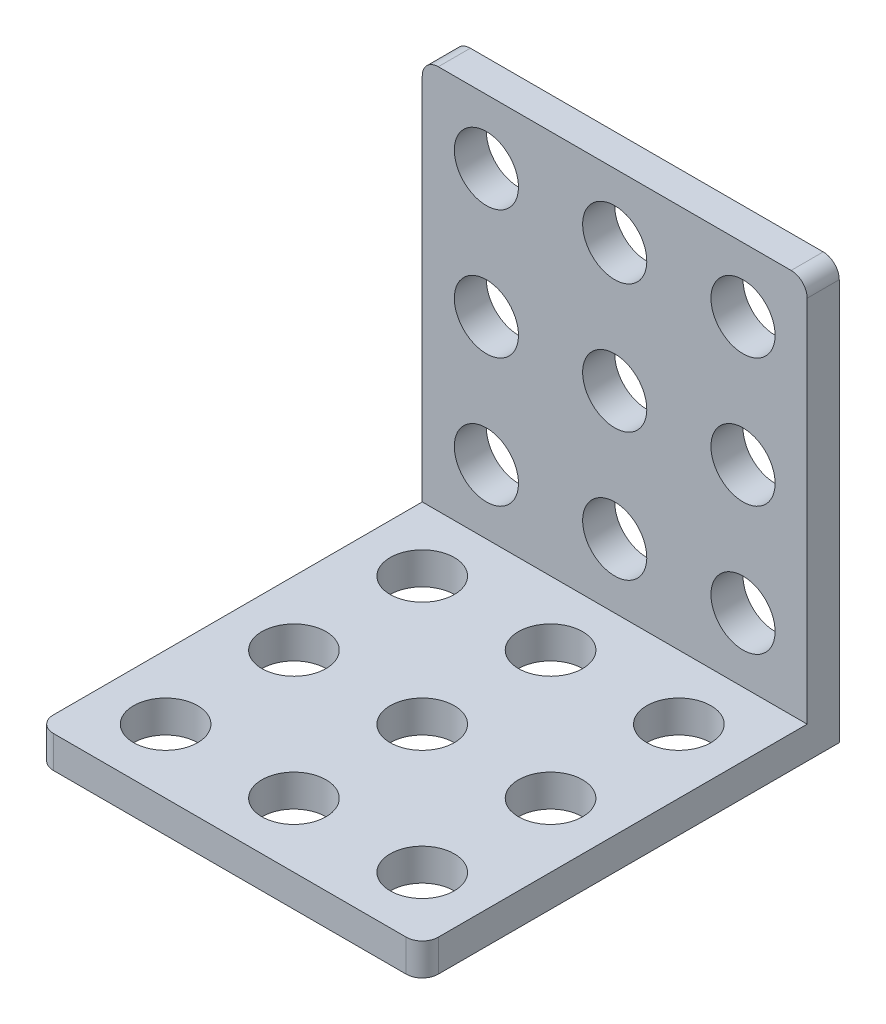
SolidWorks part; units mm, degrees
ref_plane "Спереди" through (0, 0, 0) normal (0, 0, 1) x (1, 0, 0)
ref_plane "Сверху" through (0, 0, 0) normal (0, 1, 0) x (1, 0, 0)
ref_plane "Справа" through (0, 0, 0) normal (1, 0, 0) x (0, 0, -1)
sketch "Эскиз1" plane through (0, 0, 0) normal (1, 0, 0) x (0, 0, -1)
  line L0 (0, 0) -> (-26, 0)
  line L1 (-26, 0) -> (-26, 2)
  line L2 (-26, 2) -> (-2, 2)
  line L3 (-2, 2) -> (-2, 26)
  line L4 (-2, 26) -> (0, 26)
  line L5 (0, 26) -> (0, 0)
  dimension "D1" = 26
  dimension "D2" = 26
  dimension "D3" = 2
extrude "Бобышка-Вытянуть1" add sketch "Эскиз1" along normal blind 24
sketch "Эскиз2" plane through (0, 0, 0) normal (0, 0, 1) x (1, 0, 0)
  line L0 (12, 2) -> (12, 26) construction
  line L1 (0, 26) -> (24, 26) construction
  line L2 (0, 26) -> (0, 2) construction
  line L3 (0, 2) -> (24, 2) construction
  line L4 (24, 26) -> (24, 2) construction
  line L5 (0, 14) -> (24, 14) construction
  line L6 (0, 26) -> (0, 25)
  line L7 (0, 26) -> (1, 26)
  line L8 (24, 26) -> (23, 26)
  line L9 (24, 26) -> (24, 25)
  circle A0 centre (12, 14) radius 2
  circle A1 centre (4, 14) radius 2
  circle A2 centre (20, 14) radius 2
  circle A3 centre (12, 22) radius 2
  circle A4 centre (4, 22) radius 2
  circle A5 centre (20, 22) radius 2
  circle A6 centre (12, 6) radius 2
  circle A7 centre (4, 6) radius 2
  circle A8 centre (20, 6) radius 2
  arc A9 (1, 26) -> (0, 25) centre (1, 25) ccw
  arc A10 (23, 26) -> (24, 25) centre (23, 25) cw
  dimension "D1" = 4
  dimension "D6" = 8
  dimension "D7" = 1
  dimension "D2" = 8
  dimension "D4" = 8
  dimension "D8" = 1
  dimension "D3" = 2
  dimension "D5" = 2
extrude "Вырез-Вытянуть1" cut sketch "Эскиз2" against normal blind 24 and the other way blind 24
sketch "Эскиз3" plane through (0, 0, 0) normal (0, 1, 0) x (1, 0, 0)
  line L0 (12, -2) -> (12, -26) construction
  line L1 (0, -2) -> (24, -2) construction
  line L2 (0, -2) -> (0, -26) construction
  line L3 (0, -26) -> (24, -26) construction
  line L4 (24, -2) -> (24, -26) construction
  line L5 (0, -14) -> (24, -14) construction
  line L6 (0, -25) -> (0, -26)
  line L7 (0, -26) -> (1, -26)
  line L8 (24, -26) -> (23, -26)
  line L9 (24, -25) -> (24, -26)
  circle A0 centre (12, -14) radius 2
  circle A1 centre (4, -14) radius 2
  circle A2 centre (20, -14) radius 2
  circle A3 centre (12, -6) radius 2
  circle A4 centre (4, -6) radius 2
  circle A5 centre (20, -6) radius 2
  circle A6 centre (12, -22) radius 2
  circle A7 centre (4, -22) radius 2
  circle A8 centre (20, -22) radius 2
  arc A9 (1, -26) -> (0, -25) centre (1, -25) cw
  arc A10 (23, -26) -> (24, -25) centre (23, -25) ccw
  dimension "D1" = 4
  dimension "D2" = 8
  dimension "D4" = 8
  dimension "D6" = 8
  dimension "D8" = 1
  dimension "D7" = 1
  dimension "D3" = 2
  dimension "D5" = 2
extrude "Вырез-Вытянуть2" cut sketch "Эскиз3" against normal blind 24 and the other way blind 24
